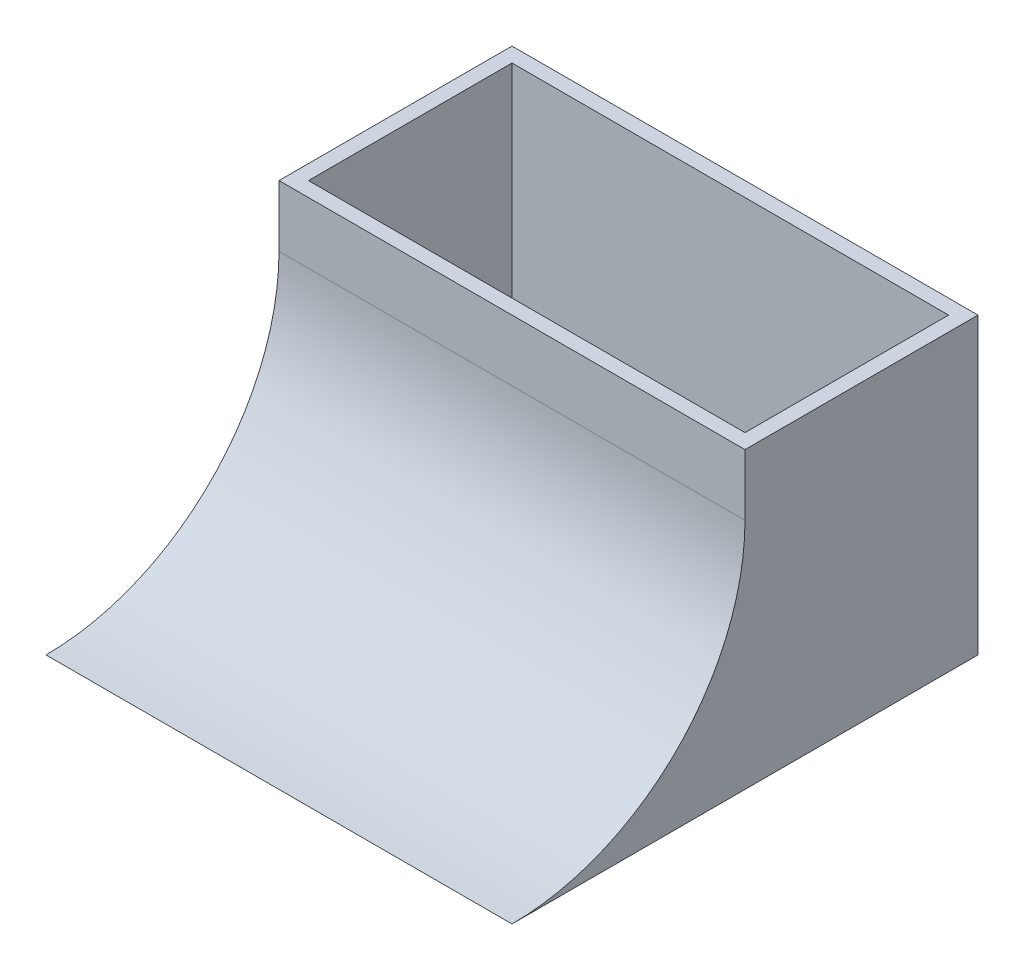
SolidWorks part; units mm, degrees
ref_plane "Plano frontal" through (0, 0, 0) normal (0, 0, 1) x (1, 0, 0)
ref_plane "Plano superior" through (0, 0, 0) normal (0, 1, 0) x (1, 0, 0)
ref_plane "Plano direito" through (0, 0, 0) normal (1, 0, 0) x (0, 0, -1)
sketch "Esboço3" plane through (0, 0, 0) normal (1, 0, 0) x (0, 0, -1)
  line L1 (47.5, 47.5) -> (-47.5, 47.5)
  line L2 (47.5, 47.5) -> (47.5, -47.5)
  line L3 (47.5, -47.5) -> (-47.5, -47.5)
  line L4 (-47.5, 47.5) -> (-47.5, -47.5)
  line L5 (47.5, 47.5) -> (-47.5, -47.5) construction
  line L6 (47.5, -47.5) -> (-47.5, 47.5) construction
  point P0 (0, 0)
  dimension "D1" = 95
  dimension "D2" = 95
extrude "Ressalto-extrusão2" add sketch "Esboço3" along normal mid plane 95
sketch "Esboço4" plane through (47.5, 0, 0) normal (1, 0, 0) x (0, 0, -1)
  line L0 (-47.5, 47.5) -> (-47.5, -47.5) construction
  circle A0 centre (-47.5, 0) radius 47.5
extrude "Corte-extrusão1" cut sketch "Esboço4" against normal through all both and the other way through all
sketch "Esboço5" plane through (0, 0, 0) normal (1, 0, 0) x (0, 0, -1)
  line L0 (0, 0) -> (0, 47.5)
  line L1 (47.5, 47.5) -> (-47.5, 47.5) construction
  line L2 (0, 47.5) -> (-47.5, 47.5)
  line L3 (-47.5, 47.5) -> (0, 0)
extrude "Corte-extrusão2" cut sketch "Esboço5" against normal through all both and the other way through all
sketch "Esboço6" plane through (0, 0, 0) normal (1, 0, 0) x (0, 0, -1)
  line L0 (0, 47.5) -> (0, 12.5)
  line L1 (0, 0) -> (0, 47.5) construction
  line L2 (0, 12.5) -> (47.5, 12.5)
  line L3 (47.5, -47.5) -> (47.5, 47.5) construction
  line L4 (47.5, 12.5) -> (47.5, 47.5)
  line L5 (47.5, 47.5) -> (0, 47.5)
  dimension "D1" = 35
extrude "Corte-extrusão3" cut sketch "Esboço6" against normal through all both and the other way through all
sketch "Esboço7" plane through (0, 12.5, 0) normal (0, 1, 0) x (1, 0, 0)
  line L0 (0, 0) -> (0, 47.5) construction
  line L1 (-47.5, 47.5) -> (47.5, 47.5) construction
  line L2 (-47.5, 0) -> (47.5, 0) construction
  line L3 (-44.5, 3) -> (44.5, 3)
  line L4 (-44.5, 3) -> (-44.5, 44.5)
  line L5 (-44.5, 44.5) -> (44.5, 44.5)
  line L6 (44.5, 3) -> (44.5, 44.5)
  line L7 (-44.5, 3) -> (44.5, 44.5) construction
  line L8 (-44.5, 44.5) -> (44.5, 3) construction
  line L9 (-47.5, 0) -> (-47.5, 47.5) construction
  point P5 (0, 23.75)
  dimension "D1" = 3
  dimension "D2" = 3
extrude "Corte-extrusão4" cut sketch "Esboço7" against normal blind 57
sketch "Esboço10" plane through (47.5, 0, 0) normal (1, 0, 0) x (0, 0, -1)
  line L0 (47.5, -47.5) -> (0, 0) construction
  line L2 (0, 0) -> (0, -47.5) construction
  line L3 (-47.5, -47.5) -> (47.5, -47.5) construction
  line L4 (0, -47.5) -> (47.5, -47.5) construction
